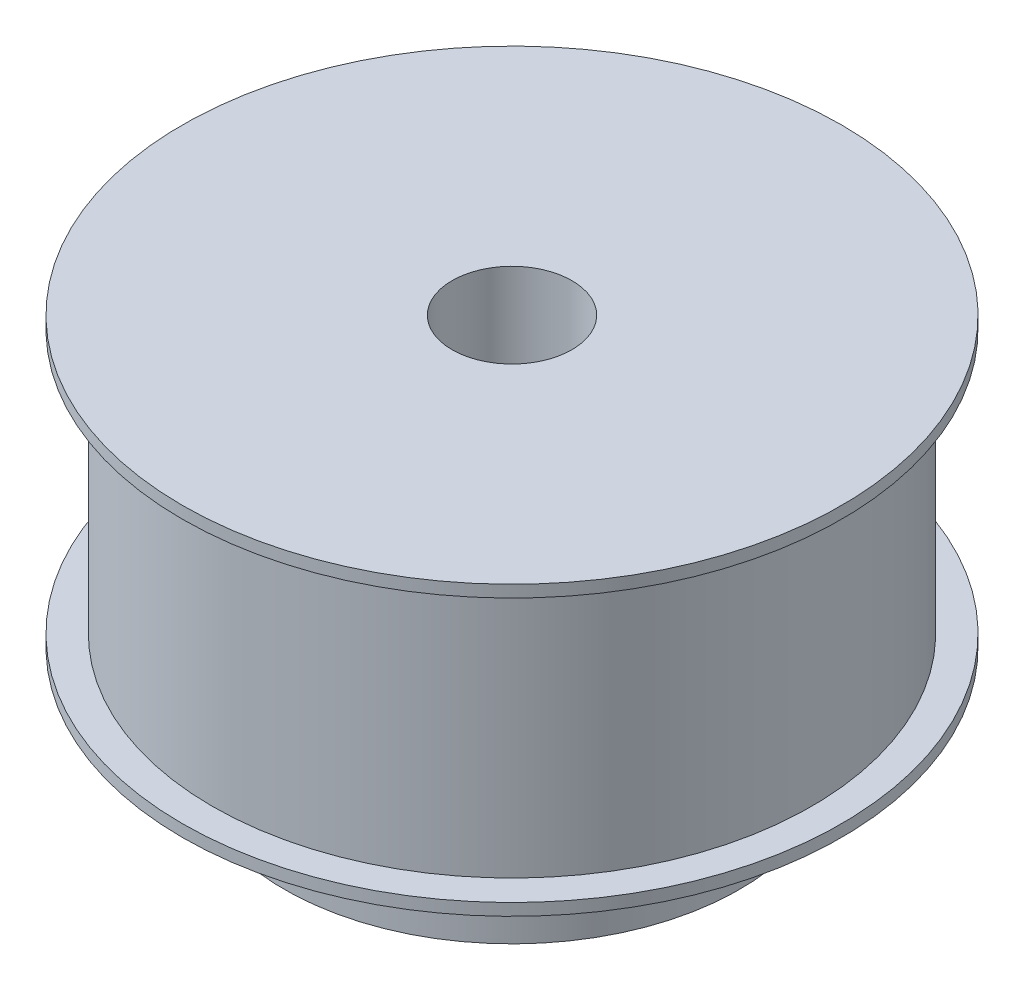
SolidWorks part; units mm, degrees
ref_plane "Front Plane" through (0, 0, 0) normal (0, 0, 1) x (1, 0, 0)
ref_plane "Top Plane" through (0, 0, 0) normal (0, 1, 0) x (1, 0, 0)
ref_plane "Right Plane" through (0, 0, 0) normal (1, 0, 0) x (0, 0, -1)
sketch "Sketch1" plane through (0, 0, 0) normal (0, 0, 1) x (1, 0, 0)
  line L0 (-25, 0) -> (0, 0) construction
  line L10 (0, 0) -> (0, 22)
  line L12 (-25, 0) -> (-25, 22)
  line L13 (-25, 22) -> (-27.5, 22)
  line L14 (0, 22) -> (0, 23)
  line L15 (0, 23) -> (-27.5, 23)
  line L16 (-27.5, 22) -> (-27.5, 23)
  line L17 (-25, 0) -> (-27.5, 0)
  line L18 (0, 0) -> (0, -1)
  line L19 (-19, -1) -> (-27.5, -1)
  line L20 (-27.5, 0) -> (-27.5, -1)
  line L22 (0, -1) -> (0, -9)
  line L23 (0, -9) -> (-19, -9)
  line L24 (-19, -1) -> (-19, -9)
  line L25 (-19, -1) -> (0, -1) construction
  line L26 (-25, 22) -> (0, 22) construction
  dimension "D1" = 1
  dimension "D2" = 27.5
  dimension "D3" = 8
  dimension "D4" = 19
  dimension "D5" = 25
  dimension "D6" = 22
  dimension "D7" = 27.5
  dimension "D8" = 1
revolve "Revolve1" add sketch "Sketch1" angle 360 about L10
sketch "Sketch2" plane through (0, 23, 0) normal (0, 1, 0) x (1, 0, 0)
  circle A0 centre (0, 0) radius 5
  point P2 (0, 0)
  point P3 (-2.3222, -2.4519)
  dimension "D1" = 10
extrude "Cut-Extrude1" cut sketch "Sketch2" against normal blind 34
